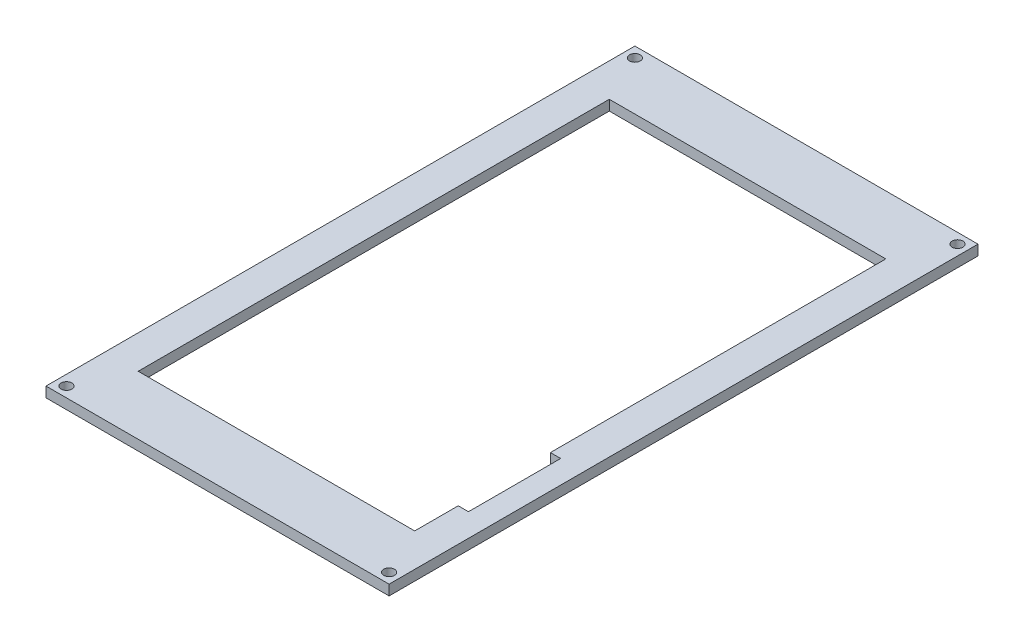
SolidWorks part; units mm, degrees
ref_plane "前视基准面" through (0, 0, 0) normal (0, 0, 1) x (1, 0, 0)
ref_plane "上视基准面" through (0, 0, 0) normal (0, 1, 0) x (1, 0, 0)
ref_plane "右视基准面" through (0, 0, 0) normal (1, 0, 0) x (0, 0, -1)
sketch "草图1" plane through (0, 0, 0) normal (0, 1, 0) x (1, 0, 0)
  line L0 (0, 0) -> (67, -115) construction
  line L1 (0, 0) -> (67, 0)
  line L2 (0, 0) -> (0, -115)
  line L3 (0, -115) -> (67, -115)
  line L4 (67, 0) -> (67, -115)
  line L5 (67, 0) -> (0, -115) construction
  line L6 (0, -2) -> (67, -2) construction
  line L7 (6.5, -11.5) -> (60.5, -11.5)
  line L8 (6.5, -11.5) -> (6.5, -103.5)
  line L9 (6.5, -103.5) -> (60.5, -103.5)
  line L10 (60.5, -11.5) -> (60.5, -103.5)
  line L11 (6.5, -11.5) -> (60.5, -103.5) construction
  line L12 (6.5, -103.5) -> (60.5, -11.5) construction
  line L13 (60.5, -95) -> (62.5, -95)
  line L14 (60.5, -95) -> (60.5, -77)
  line L15 (60.5, -77) -> (62.5, -77)
  line L16 (62.5, -95) -> (62.5, -77)
  line L17 (0, -113) -> (67, -113) construction
  line L18 (2, 0) -> (2, -115) construction
  line L19 (65, 0) -> (65, -115) construction
  circle A0 centre (2, -2) radius 1.05
  circle A1 centre (65, -2) radius 1.05
  circle A2 centre (2, -113) radius 1.05
  circle A3 centre (65, -113) radius 1.05
  point P5 (33.5, -57.5)
  dimension "D12" = 2.1
  dimension "D13" = 2.1
  dimension "D14" = 2.1
  dimension "D15" = 2.1
  dimension "D1" = 67
  dimension "D2" = 115
  dimension "D3" = 54
  dimension "D4" = 92
  dimension "D5" = 8.5
  dimension "D6" = 2
  dimension "D7" = 18
  dimension "D8" = 2
  dimension "D9" = 2
  dimension "D10" = 2
  dimension "D11" = 2
extrude "凸台-拉伸1" add sketch "草图1" along normal blind 2 contours L4 L1 L2 L3 L16 L13 L10 L9 L8 L7 L15
